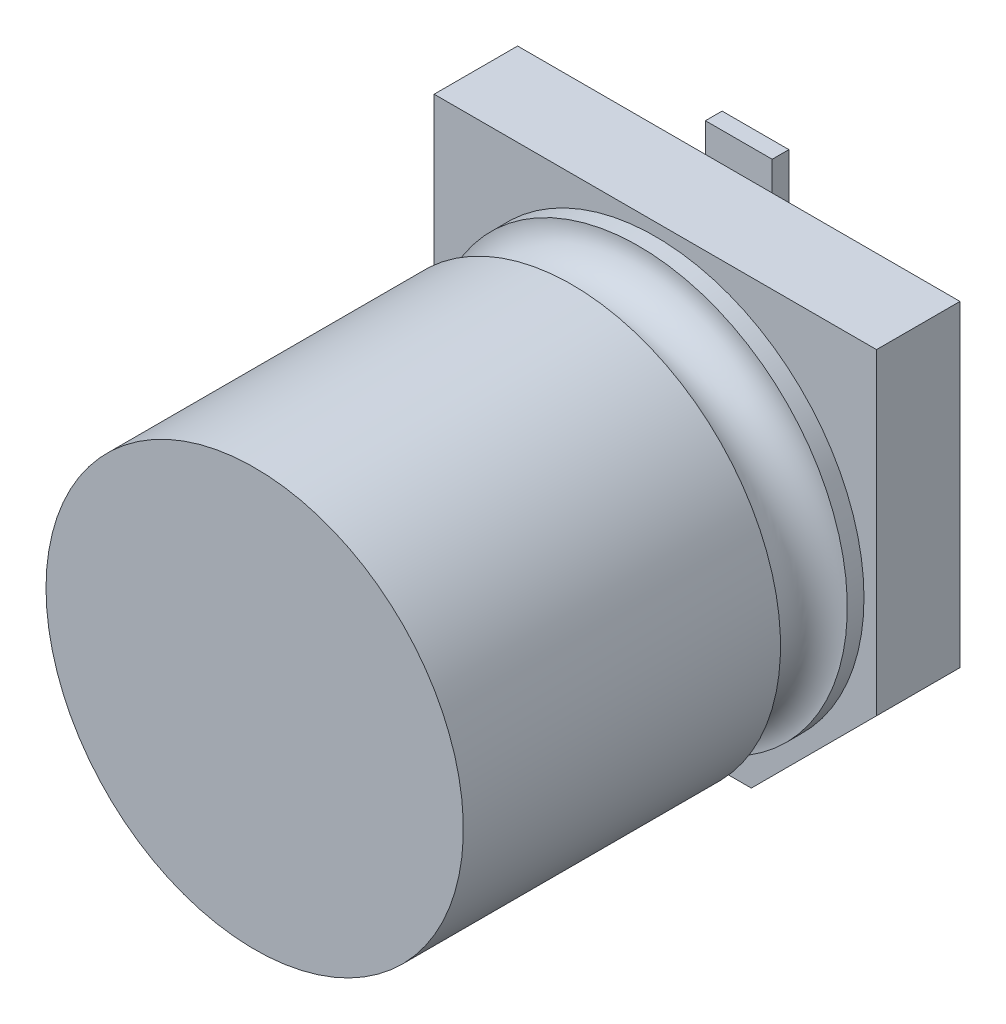
SolidWorks part; units mm, degrees
ref_plane "Plan de face" through (0, 0, 0) normal (0, 0, 1) x (1, 0, 0)
ref_plane "Plan de dessus" through (0, 0, 0) normal (0, 1, 0) x (1, 0, 0)
ref_plane "Plan de droite" through (0, 0, 0) normal (1, 0, 0) x (0, 0, -1)
sketch "Sketch1" plane through (0, 0, 0) normal (0, 0, 1) x (1, 0, 0)
  line L0 (-2.65, 2.65) -> (2.65, 2.65)
  line L1 (0, 2.5288) -> (0, 0) construction
  line L2 (0, 0) -> (1.6891, 0) construction
  line L3 (-2.65, 2.65) -> (-2.65, -1.15)
  line L4 (-2.65, -1.15) -> (-1.15, -2.65)
  line L5 (-1.15, -2.65) -> (1.15, -2.65)
  line L6 (1.15, -2.65) -> (2.65, -1.15)
  line L7 (2.65, -1.15) -> (2.65, 2.65)
  point P9 (0, 0)
  point P11 (0, 0)
  dimension "D1" = 5.3
  dimension "D2" = 5.3
  dimension "D3" = 1.5
extrude "Boss-Extrude1" add sketch "Sketch1" along normal blind 1 from offset 0.2
sketch "Sketch2" plane through (0, 0, 0) normal (1, 0, 0) x (0, 0, -1)
  line L0 (0, 0) -> (-12.2426, 0) construction
  line L1 (-6, 0) -> (-6, 2.5)
  line L2 (-6, 2.5) -> (-2.2, 2.5)
  line L3 (-1.2, 2.5) -> (-1.2, 0)
  line L4 (-1.2, 0) -> (-6, 0)
  line L5 (-1.2, -1.15) -> (-1.2, 2.65) construction
  line L6 (-1.4, 2.5) -> (-1.2, 2.5)
  arc A0 (-2.2, 2.5) -> (-1.4, 2.5) centre (-1.8, 2.5) ccw
  point P12 (0, 0)
  dimension "D3" = 0.8
  dimension "D1" = 5
  dimension "D2" = 6
  dimension "D4" = 0.2
revolve "Revolve1" add sketch "Sketch2" angle 360 about L0
sketch "Sketch3" plane through (0, 0, 0) normal (0, 0, 1) x (1, 0, 0)
  line L0 (0, 0) -> (0, -1.6902) construction
  line L2 (0.4, -1.1) -> (0.4, -3)
  line L3 (0.4, -3) -> (-0.4, -3)
  line L4 (-0.4, -1.1) -> (-0.4, -3)
  arc A0 (0.4, -1.1) -> (-0.4, -1.1) centre (0, -1.1) ccw
  dimension "D2" = 1.1
  dimension "D1" = 0.8
  dimension "D3" = 3
extrude "Boss-Extrude2" add sketch "Sketch3" along normal up to surface (0.2 mm away) up to face at (0, -0.3833, 0.2)
mirror "Mirror1" about plane through (0, 0, 0) normal (0, 1, 0) of "Boss-Extrude2"
